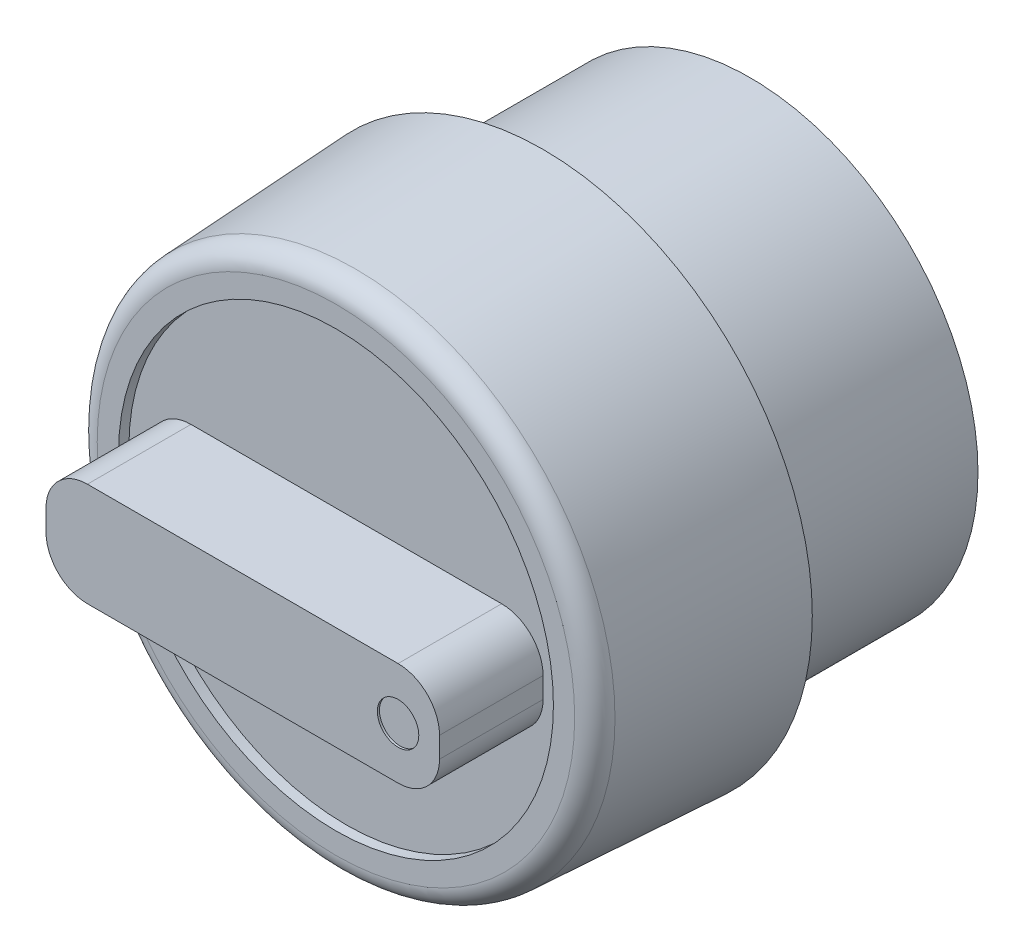
SolidWorks part; units mm, degrees
material "SKD11淬火HRC56－60"
ref_plane "前基準面" through (0, 0, 0) normal (0, 0, 1) x (1, 0, 0)
ref_plane "上基準面" through (0, 0, 0) normal (0, 1, 0) x (1, 0, 0)
ref_plane "右基準面" through (0, 0, 0) normal (1, 0, 0) x (0, 0, -1)
sketch "草图1" plane through (0, 0, 0) normal (0, 0, 1) x (1, 0, 0)
  circle A0 centre (0, 0) radius 11
  dimension "D1" = 22
extrude "凸台-拉伸1" add sketch "草图1" along normal blind 10
sketch "草图2" plane through (0, 0, 10) normal (0, 0, 1) x (1, 0, 0)
  circle A0 centre (0, 0) radius 13
  dimension "D1" = 26
extrude "凸台-拉伸2" add sketch "草图2" along normal blind 10 draft 3
fillet "圆角1" radius 1 1 edges at (12.4759, 0, 20)
sketch "草图3" plane through (0, 0, 20) normal (0, 0, 1) x (1, 0, 0)
  circle A0 centre (0, 0) radius 10.5
  dimension "D1" = 21
extrude "切除-拉伸1" cut sketch "草图3" against normal blind 0.5
sketch "草图4" plane through (0, 0, 19.5) normal (0, 0, 1) x (1, 0, 0)
  line L0 (0, 0) -> (9.1634, 0) construction
  line L1 (-9.5, 2.5) -> (9.5, 2.5)
  line L2 (-9.5, 2.5) -> (-9.5, -2.5)
  line L3 (-9.5, -2.5) -> (9.5, -2.5)
  line L4 (9.5, 2.5) -> (9.5, -2.5)
  line L5 (0, 0) -> (0, 5.2568) construction
  dimension "D1" = 5
  dimension "D2" = 19
extrude "凸台-拉伸4" add sketch "草图4" along normal blind 5
fillet "圆角3" radius 2 4 edges at (9.5, 2.5, 22) (9.5, -2.5, 22) (-9.5, 2.5, 22) (-9.5, -2.5, 22)
sketch "草图5" plane through (0, 0, 24.5) normal (0, 0, 1) x (1, 0, 0)
  line L0 (9.5, 0) -> (4.9455, 0) construction
  line L1 (9.5, -0.5) -> (9.5, 0.5) construction
  circle A0 centre (7.5, 0) radius 1
  dimension "D1" = 2
  dimension "D2" = 2
extrude "切除-拉伸2" cut sketch "草图5" against normal blind 0.1
